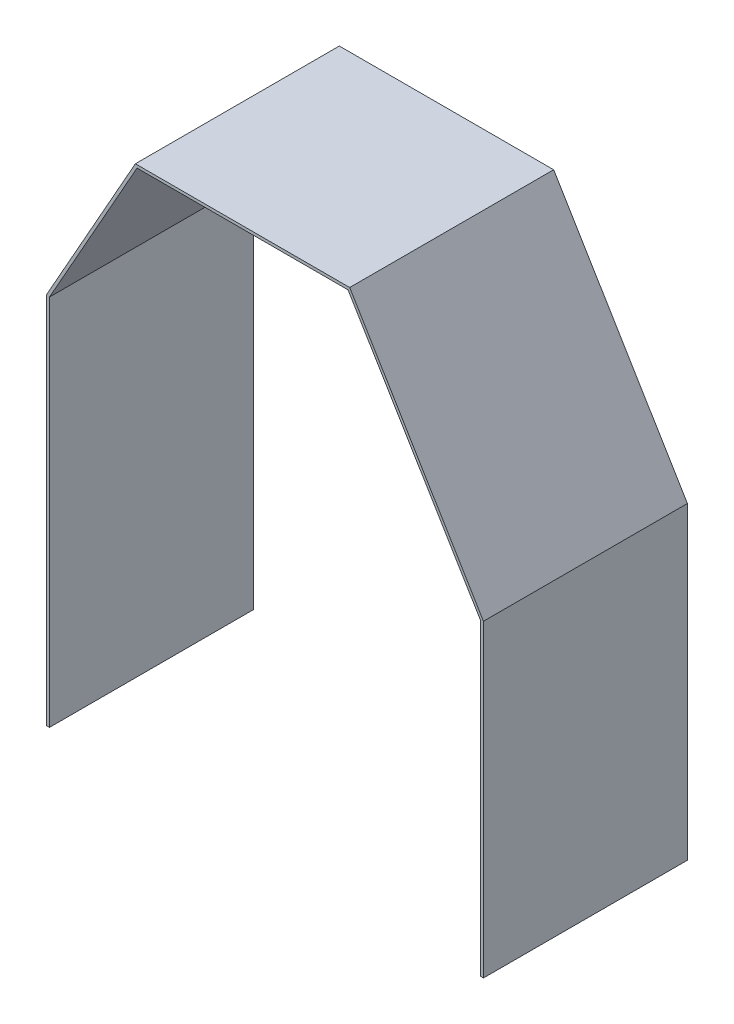
SolidWorks part; units mm, degrees
ref_plane "Спереди" through (0, 0, 0) normal (0, 0, 1) x (1, 0, 0)
ref_plane "Сверху" through (0, 0, 0) normal (0, 1, 0) x (1, 0, 0)
ref_plane "Справа" through (0, 0, 0) normal (1, 0, 0) x (0, 0, -1)
sketch "Эскиз1" plane through (0, 0, 0) normal (0, 0, 1) x (1, 0, 0)
  line L0 (59.8075, 369.7469) -> (209.0124, 369.7469)
  line L2 (-2, 0) -> (-2, 260)
  line L3 (59.8075, 369.7469) -> (-2, 260)
  line L4 (302.135, 0) -> (302.135, 215.0862)
  line L5 (209.0124, 369.7469) -> (302.135, 215.0862)
extrude "Вытянуть-Тонкостенный1" add sketch "Эскиз1" against normal blind 142 thin
